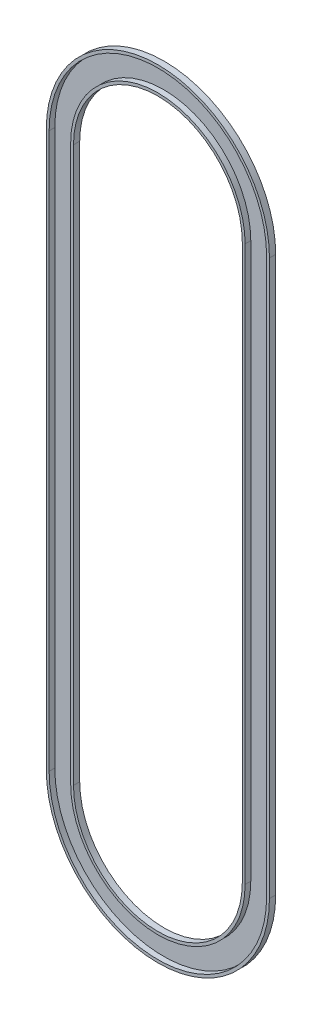
SolidWorks part; units mm, degrees
ref_plane "Front Plane" through (0, 0, 0) normal (0, 0, 1) x (1, 0, 0)
ref_plane "Top Plane" through (0, 0, 0) normal (0, 1, 0) x (1, 0, 0)
ref_plane "Right Plane" through (0, 0, 0) normal (1, 0, 0) x (0, 0, -1)
sketch "Sketch1" plane through (0, 0, 0) normal (0, 0, 1) x (1, 0, 0)
  line L0 (-745, 5402.1689) -> (-745, 505.1689)
  line L1 (745, 5402.1689) -> (745, 505.1689)
  line L2 (-985, 5402.1689) -> (-985, 505.1689)
  line L3 (985, 5402.1689) -> (985, 505.1689)
  arc A0 (745, 5402.1689) -> (-745, 5402.1689) centre (0, 5402.1689) ccw
  arc A1 (-745, 505.1689) -> (745, 505.1689) centre (0, 505.1689) ccw
  arc A2 (-985, 505.1689) -> (985, 505.1689) centre (0, 505.1689) ccw
  arc A3 (985, 5402.1689) -> (-985, 5402.1689) centre (0, 5402.1689) ccw
  dimension "D1" = 1490
  dimension "D2" = 1490
  dimension "D3" = 4897
  dimension "D4" = 240
extrude "Boss-Extrude1" add sketch "Sketch1" along normal blind 5
sketch "Sketch2" plane through (0, 0, 5) normal (0, 0, 1) x (1, 0, 0)
  line L0 (745, 505.1689) -> (745, 5402.1689) construction
  line L1 (-745, 5402.1689) -> (-745, 505.1689) construction
  line L2 (745, 505.1689) -> (745, 5402.1689)
  line L3 (-745, 5402.1689) -> (-745, 505.1689)
  line L4 (-770, 5402.1689) -> (-770, 505.1689)
  line L5 (770, 505.1689) -> (770, 5402.1689)
  arc A0 (-745, 505.1689) -> (745, 505.1689) centre (0, 505.1689) ccw construction
  arc A1 (745, 5402.1689) -> (-745, 5402.1689) centre (0, 5402.1689) ccw construction
  arc A2 (-745, 505.1689) -> (745, 505.1689) centre (0, 505.1689) ccw
  arc A3 (745, 5402.1689) -> (-745, 5402.1689) centre (0, 5402.1689) ccw
  arc A4 (-770, 505.1689) -> (770, 505.1689) centre (0, 505.1689) ccw
  arc A5 (770, 5402.1689) -> (-770, 5402.1689) centre (0, 5402.1689) ccw
  dimension "D1" = 25
extrude "Boss-Extrude2" add sketch "Sketch2" along normal blind 50
sketch "Sketch3" plane through (0, 0, 5) normal (0, 0, 1) x (1, 0, 0)
  line L0 (985, 505.1689) -> (985, 5402.1689) construction
  line L1 (-985, 5402.1689) -> (-985, 505.1689) construction
  line L2 (985, 505.1689) -> (985, 5402.1689)
  line L3 (-985, 5402.1689) -> (-985, 505.1689)
  line L4 (-960, 5402.1689) -> (-960, 505.1689)
  line L5 (960, 505.1689) -> (960, 5402.1689)
  arc A0 (-985, 505.1689) -> (985, 505.1689) centre (0, 505.1689) ccw construction
  arc A1 (985, 5402.1689) -> (-985, 5402.1689) centre (0, 5402.1689) ccw construction
  arc A2 (-985, 505.1689) -> (985, 505.1689) centre (0, 505.1689) ccw
  arc A3 (985, 5402.1689) -> (-985, 5402.1689) centre (0, 5402.1689) ccw
  arc A4 (960, 5402.1689) -> (-960, 5402.1689) centre (0, 5402.1689) ccw
  arc A5 (-960, 505.1689) -> (960, 505.1689) centre (0, 505.1689) ccw
  dimension "D1" = 25
extrude "Boss-Extrude3" add sketch "Sketch3" along normal blind 50
